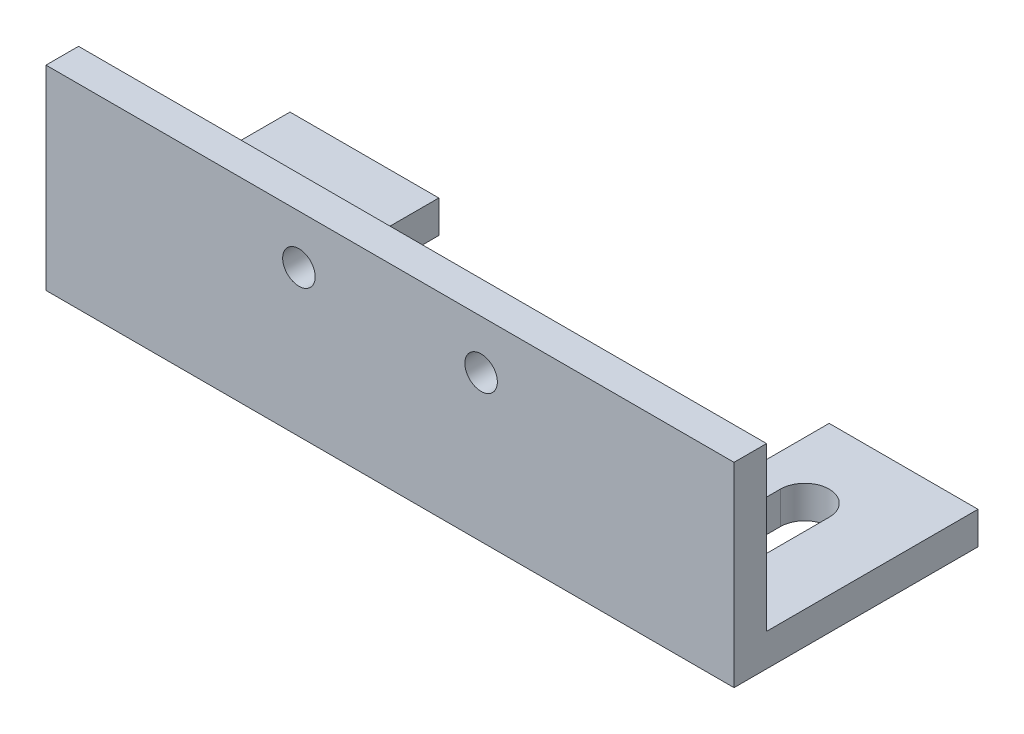
SolidWorks part; units mm, degrees
ref_plane "Płaszczyzna przednia" through (0, 0, 0) normal (0, 0, 1) x (1, 0, 0)
ref_plane "Płaszczyzna górna" through (0, 0, 0) normal (0, 1, 0) x (1, 0, 0)
ref_plane "Płaszczyzna prawa" through (0, 0, 0) normal (1, 0, 0) x (0, 0, -1)
sketch "Szkic1" plane through (0, 0, 0) normal (0, 1, 0) x (1, 0, 0)
  line L0 (0, 7.5) -> (0, -7.5) construction
  line L1 (-21.15, 7.5) -> (-12, 7.5)
  line L2 (-21.15, 7.5) -> (-21.15, -7.5)
  line L3 (-21.15, -7.5) -> (21.15, -7.5)
  line L4 (21.15, 7.5) -> (21.15, -7.5)
  line L5 (-21.15, 7.5) -> (21.15, -7.5) construction
  line L6 (-21.15, -7.5) -> (21.15, 7.5) construction
  line L7 (-15.5, 2.5) -> (-15.5, -2.5) construction
  line L8 (-14, 2.5) -> (-14, -2.5)
  line L9 (-17, 2.5) -> (-17, -2.5)
  line L10 (15.5, 2.5) -> (15.5, -2.5) construction
  line L11 (17, 2.5) -> (17, -2.5)
  line L12 (14, 2.5) -> (14, -2.5)
  line L13 (12, 7.5) -> (12, -2.5)
  line L14 (12, -2.5) -> (-12, -2.5)
  line L15 (-12, -2.5) -> (-12, 7.5)
  line L16 (12, 7.5) -> (21.15, 7.5)
  arc A3 (-14, 2.5) -> (-17, 2.5) centre (-15.5, 2.5) ccw
  arc A4 (-17, -2.5) -> (-14, -2.5) centre (-15.5, -2.5) ccw
  arc A5 (17, 2.5) -> (14, 2.5) centre (15.5, 2.5) ccw
  arc A6 (14, -2.5) -> (17, -2.5) centre (15.5, -2.5) ccw
  point P0 (0, 0)
  point P10 (-15.5, 0)
  point P18 (15.5, 0)
  dimension "D3" = 5
  dimension "D4" = 1.5
  dimension "D1" = 42.3
  dimension "D2" = 15
  dimension "D5" = 31
  dimension "D6" = 5
  dimension "D7" = 24
extrude "Dodanie-wyciągnięcie1" add sketch "Szkic1" along normal blind 2
sketch "Szkic4" plane through (0, 0, 7.5) normal (0, 0, 1) x (1, 0, 0)
  line L0 (0, 12) -> (0, 0) construction
  line L1 (21.15, 0) -> (-21.15, 0)
  line L2 (21.15, 0) -> (21.15, 12)
  line L3 (21.15, 12) -> (-21.15, 12)
  line L4 (-21.15, 0) -> (-21.15, 12)
  circle A0 centre (-5.6, 9) radius 1
  circle A1 centre (5.6, 9) radius 1
  point P10 (0, 0)
  dimension "D2" = 2
  dimension "D3" = 2
  dimension "D1" = 12
  dimension "D4" = 3
  dimension "D5" = 11.2
extrude "Dodanie-wyciągnięcie2" add sketch "Szkic4" against normal blind 2
